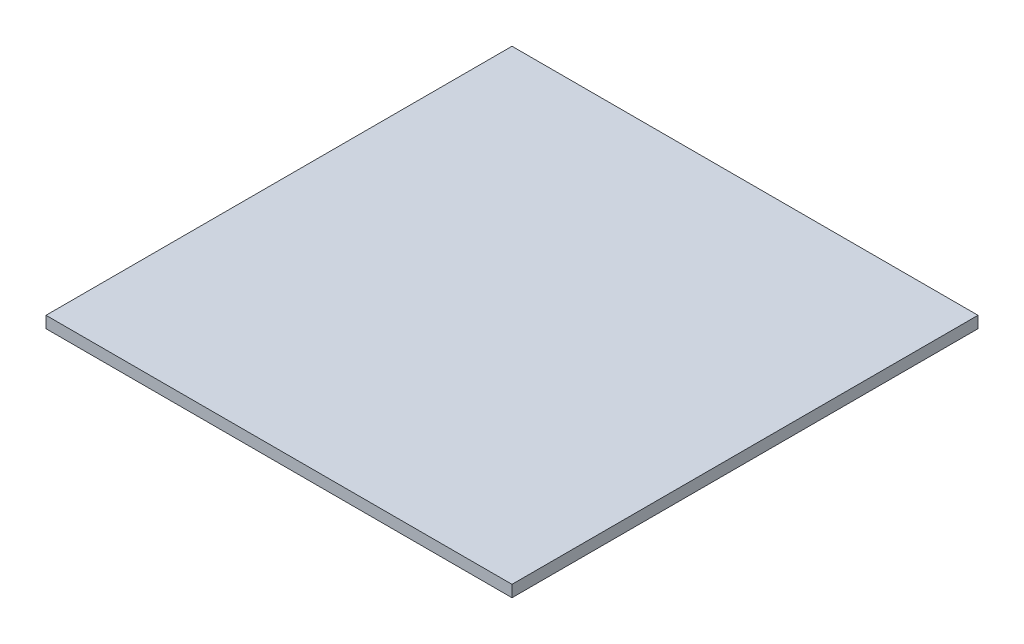
SolidWorks part; units mm, degrees
ref_plane "前视基准面" through (0, 0, 0) normal (0, 0, 1) x (1, 0, 0)
ref_plane "上视基准面" through (0, 0, 0) normal (0, 1, 0) x (1, 0, 0)
ref_plane "右视基准面" through (0, 0, 0) normal (1, 0, 0) x (0, 0, -1)
sketch "草图1" plane through (0, 0, 0) normal (0, 1, 0) x (1, 0, 0)
  line L1 (0, 0) -> (200, 0)
  line L2 (0, 0) -> (0, 200)
  line L3 (0, 200) -> (200, 200)
  line L4 (200, 0) -> (200, 200)
extrude "凸台-拉伸1" add sketch "草图1" along normal blind 5
